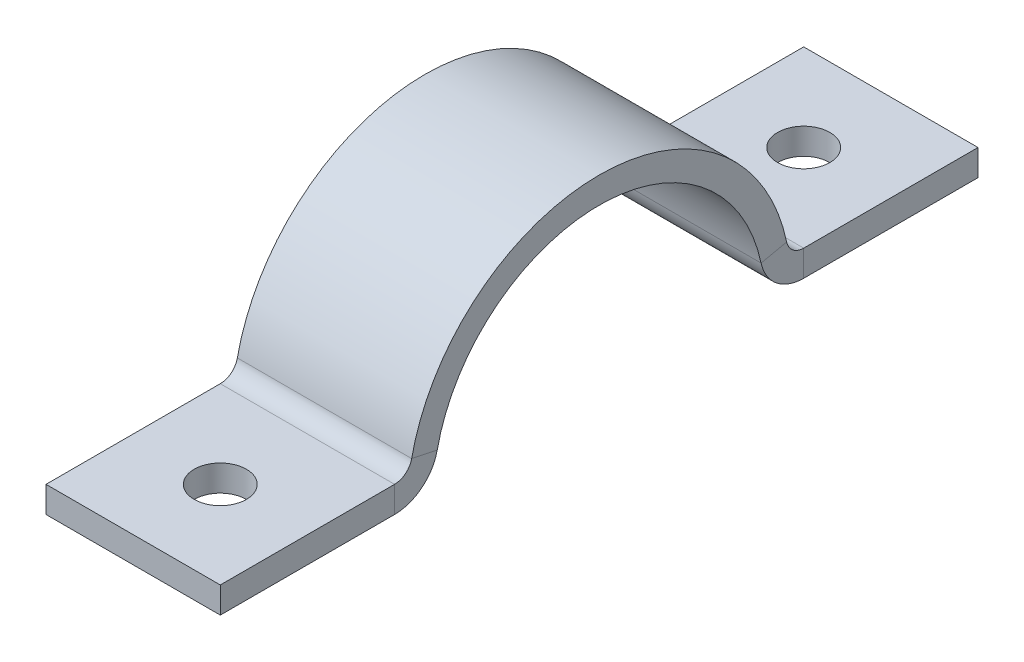
SolidWorks part; units mm, degrees
material "Galvanized Steel"
ref_plane "Front Plane" through (0, 0, 0) normal (0, 0, 1) x (1, 0, 0)
ref_plane "Top Plane" through (0, 0, 0) normal (0, 1, 0) x (1, 0, 0)
ref_plane "Right Plane" through (0, 0, 0) normal (1, 0, 0) x (0, 0, -1)
sketch "Sketch7" plane through (0, 0, 0) normal (1, 0, 0) x (0, 0, -1)
  line L11 (23.4734, 0) -> (43.4734, 0)
  line L14 (-43.4734, 0) -> (-23.4734, 0)
  arc A7 (18.5831, 3.9583) -> (-18.5831, 3.9583) centre (0, 0) ccw
  arc A10 (18.5831, 3.9583) -> (23.4734, 0) centre (23.4734, 5) ccw
  arc A11 (-18.5831, 3.9583) -> (-23.4734, 0) centre (-23.4734, 5) cw
  point P1 (0, 0)
  point P2 (0, 0)
  point P5 (0, 0)
  point P7 (0, 0)
  point P8 (0, 0)
  point P10 (0, 14.2516)
  point P21 (19, 0)
  dimension "D1" = 20
  dimension "D3" = 38
  dimension "D2" = 5
ref_plane "Plane1" through (0, 0, -43.4734) normal (0, 0, 1) x (1, 0, 0)
sketch "Sketch8" plane through (0, 0, -43.4734) normal (0, 0, 1) x (1, 0, 0)
  line L1 (10, 3) -> (-10, 3)
  line L2 (10, 3) -> (10, 0)
  line L3 (10, 0) -> (-10, 0)
  line L4 (-10, 3) -> (-10, 0)
  dimension "D1" = 3
  dimension "D2" = 20
sweep "Sweep1" add profiles "Sketch8" path "Sketch7"
sketch "Sketch10" plane through (0, 0, 0) normal (0, -1, 0) x (-1, 0, 0)
  line L0 (10, -23.4734) -> (-10, -23.4734) construction
  line L1 (10, 23.4734) -> (-10, 23.4734) construction
  circle A0 centre (0, 33.4734) radius 3
  circle A1 centre (0, -33.4734) radius 3
  point P2 (0, 30.9927)
  point P5 (0, -31.3695)
  point P10 (0, 0)
  point P11 (0, -33.4734)
  point P12 (0, -23.4734)
  dimension "D1" = 6
  dimension "D2" = 6
  dimension "D4" = 10
  dimension "D3" = 10
extrude "Cut-Extrude1" cut sketch "Sketch10" against normal through all
